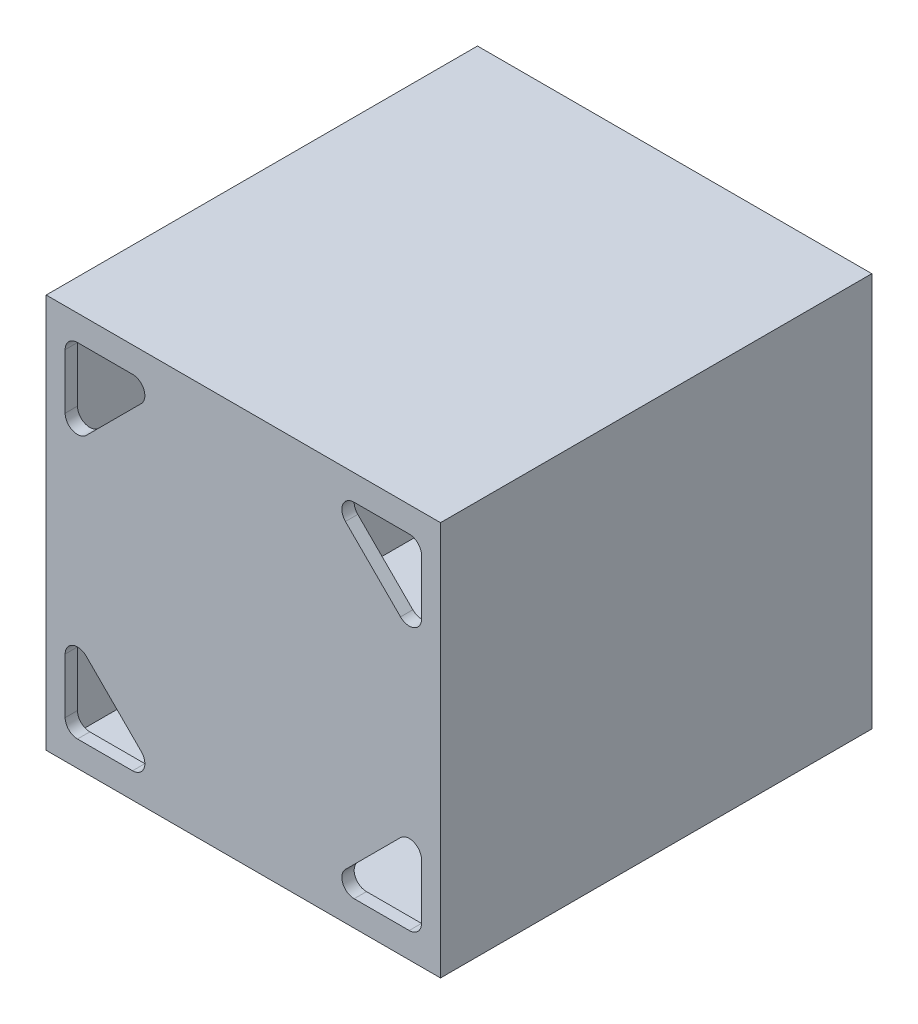
SolidWorks part; units mm, degrees
material "Custom Plastic"
ref_plane "X-Y Datum" through (0, 0, 0) normal (0, 0, 1) x (1, 0, 0)
ref_plane "X-Z Datum" through (0, 0, 0) normal (0, 1, 0) x (1, 0, 0)
ref_plane "Y-Z Datum" through (0, 0, 0) normal (1, 0, 0) x (0, 0, -1)
sketch "Sketch1" plane through (0, 0, 0) normal (0, 0, 1) x (1, 0, 0)
  line L1 (-40.64, -40.64) -> (40.64, -40.64)
  line L2 (-40.64, -40.64) -> (-40.64, 40.64)
  line L3 (-40.64, 40.64) -> (40.64, 40.64)
  line L4 (40.64, -40.64) -> (40.64, 40.64)
  line L5 (-40.64, -40.64) -> (40.64, 40.64) construction
  line L6 (-40.64, 40.64) -> (40.64, -40.64) construction
  point P0 (0, 0)
  dimension "D1" = 81.28
  dimension "D2" = 81.28
extrude "Boss-Extrude1" add sketch "Sketch1" along normal blind 88.9
shell "Shell1" thickness 2.54
sketch "Sketch4" plane through (0, 0, 0) normal (0, 0, -1) x (-1, 0, 0)
  line L14 (39.37, -39.37) -> (39.37, 39.37)
  line L15 (-39.37, -39.37) -> (39.37, -39.37)
  line L16 (-39.37, 39.37) -> (-39.37, -39.37)
  line L17 (39.37, 39.37) -> (-39.37, 39.37)
  line L18 (39.37, -39.37) -> (39.37, 39.37)
  line L19 (-39.37, -39.37) -> (39.37, -39.37)
  line L20 (-39.37, 39.37) -> (-39.37, -39.37)
  line L21 (39.37, 39.37) -> (-39.37, 39.37)
  dimension "D1" = 1.27
extrude "Cut-Extrude2" cut sketch "Sketch4" against normal blind 5.08
sketch "Sketch5" plane through (0, 0, 88.9) normal (0, 0, 1) x (1, 0, 0)
  line L0 (-36.7293, 32.8469) -> (-36.7293, 21.4969)
  line L1 (-32.3933, 19.7008) -> (-21.0432, 31.0509)
  line L2 (-22.8393, 35.3869) -> (-34.1893, 35.3869)
  line L3 (0, -43.0151) -> (0, 43.0151) construction
  line L4 (32.3933, 19.7008) -> (21.0432, 31.0509)
  line L5 (22.8393, 35.3869) -> (34.1893, 35.3869)
  line L6 (36.7293, 32.8469) -> (36.7293, 21.4969)
  line L7 (55.1739, 0) -> (-55.1739, 0) construction
  line L8 (32.3933, -19.7008) -> (21.0432, -31.0509)
  line L9 (36.7293, -32.8469) -> (36.7293, -21.4969)
  line L10 (22.8393, -35.3869) -> (34.1893, -35.3869)
  line L11 (-32.3933, -19.7008) -> (-21.0432, -31.0509)
  line L12 (-36.7293, -32.8469) -> (-36.7293, -21.4969)
  line L13 (-22.8393, -35.3869) -> (-34.1893, -35.3869)
  arc A0 (-21.0432, 31.0509) -> (-22.8393, 35.3869) centre (-22.8393, 32.8469) ccw
  arc A1 (-36.7293, 21.4969) -> (-32.3933, 19.7008) centre (-34.1893, 21.4969) ccw
  arc A2 (-36.7293, 32.8469) -> (-34.1893, 35.3869) centre (-34.1893, 32.8469) cw
  arc A3 (36.7293, 21.4969) -> (32.3933, 19.7008) centre (34.1893, 21.4969) cw
  arc A4 (21.0432, 31.0509) -> (22.8393, 35.3869) centre (22.8393, 32.8469) cw
  arc A5 (36.7293, 32.8469) -> (34.1893, 35.3869) centre (34.1893, 32.8469) ccw
  arc A6 (36.7293, -21.4969) -> (32.3933, -19.7008) centre (34.1893, -21.4969) ccw
  arc A7 (36.7293, -32.8469) -> (34.1893, -35.3869) centre (34.1893, -32.8469) cw
  arc A8 (21.0432, -31.0509) -> (22.8393, -35.3869) centre (22.8393, -32.8469) ccw
  arc A9 (-21.0432, -31.0509) -> (-22.8393, -35.3869) centre (-22.8393, -32.8469) cw
  arc A10 (-36.7293, -21.4969) -> (-32.3933, -19.7008) centre (-34.1893, -21.4969) cw
  arc A11 (-36.7293, -32.8469) -> (-34.1893, -35.3869) centre (-34.1893, -32.8469) ccw
  dimension "D1" = 2.54
extrude "Cut-Extrude3" cut sketch "Sketch5" against normal blind 17.78
